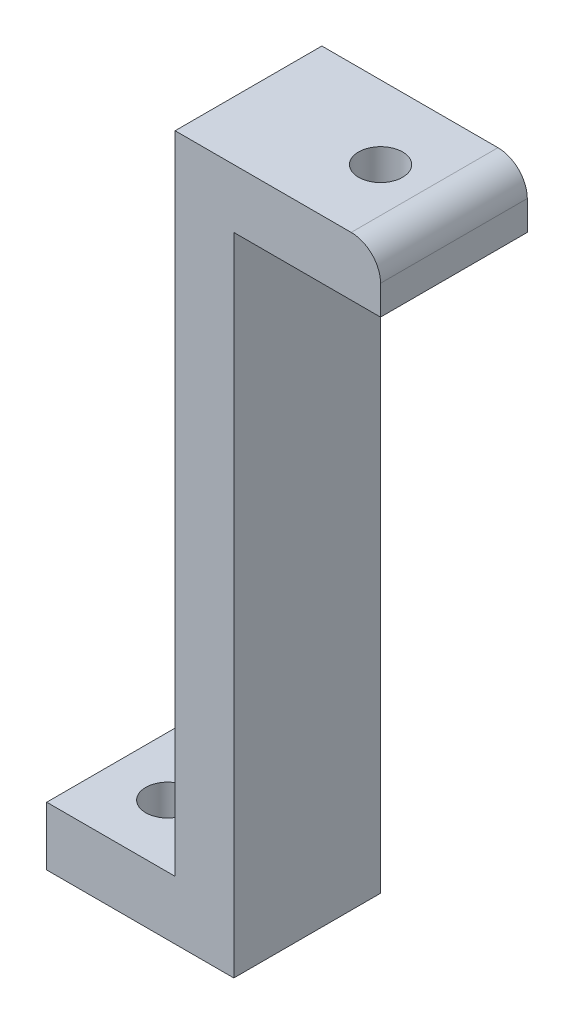
SolidWorks part; units mm, degrees
ref_plane "Front Plane" through (0, 0, 0) normal (0, 0, 1) x (1, 0, 0)
ref_plane "Top Plane" through (0, 0, 0) normal (0, 1, 0) x (1, 0, 0)
ref_plane "Right Plane" through (0, 0, 0) normal (1, 0, 0) x (0, 0, -1)
sketch "Sketch1" plane through (0, 0, 0) normal (0, 0, 1) x (1, 0, 0)
  line L0 (0, 0) -> (-14, 0)
  line L1 (-14, 0) -> (-14, -44)
  line L2 (-14, -44) -> (-22.75, -44)
  line L3 (-22.75, -44) -> (-22.75, -48)
  line L4 (-22.75, -48) -> (-10, -48)
  line L5 (-10, -48) -> (-10, -4)
  line L6 (-10, -4) -> (0, -4)
  line L7 (0, -4) -> (0, 0)
  dimension "D1" = 4
  dimension "D2" = 4
  dimension "D3" = 4
  dimension "D4" = 44
  dimension "D5" = 12.75
  dimension "D6" = 10
extrude "Boss-Extrude1" add sketch "Sketch1" along normal blind 10
sketch "Sketch2" plane through (0, -44, 0) normal (0, 1, 0) x (1, 0, 0)
  line L0 (-22.75, -10) -> (-22.75, 0) construction
  circle A0 centre (-18.75, -5.75) radius 1.5
  point P4 (-22.75, -5)
  dimension "D1" = 3
  dimension "D2" = 4
  dimension "D3" = 0.75
extrude "Cut-Extrude1" cut sketch "Sketch2" against normal blind 10
sketch "Sketch3" plane through (0, -4, 0) normal (0, -1, 0) x (-1, 0, 0)
  line L0 (0, -10) -> (0, 0) construction
  line L2 (10, -10) -> (10, 0) construction
  circle A0 centre (5, -5) radius 1.5
  point P4 (0, -5)
  dimension "D1" = 3
  dimension "D2" = 0
  dimension "D3" = 5
extrude "Cut-Extrude2" cut sketch "Sketch3" against normal blind 10
fillet "Fillet1" radius 2 1 edges at (0, 0, 5)
